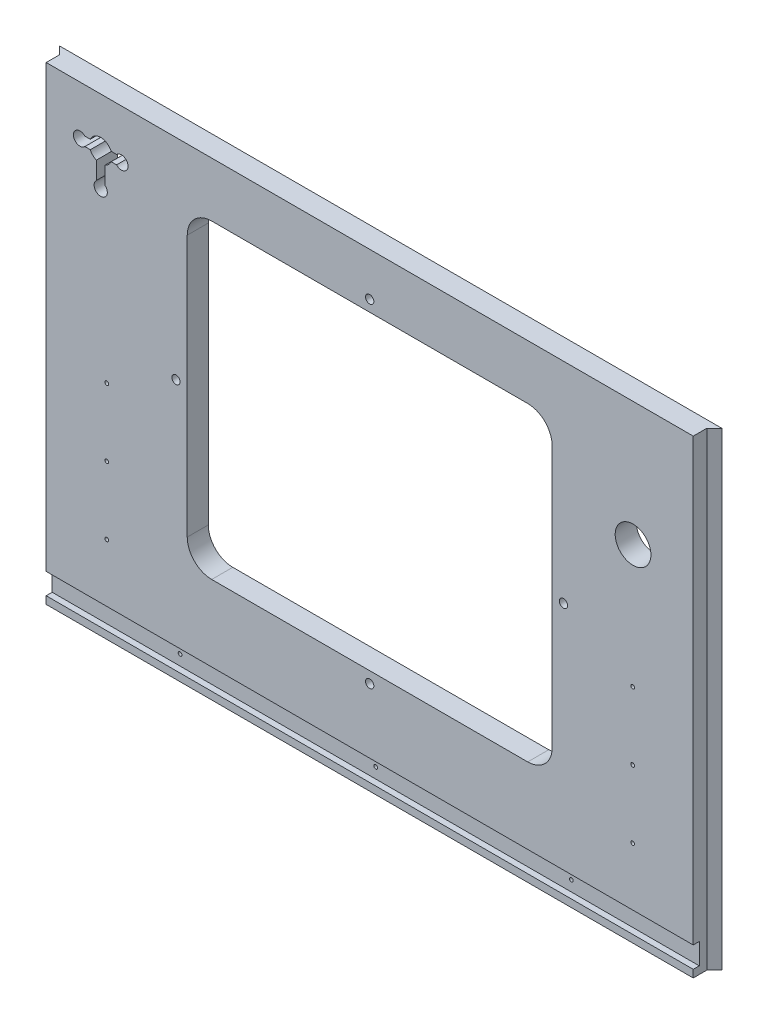
SolidWorks part; units mm, degrees
material "Pine"
ref_plane "Front Plane" through (0, 0, 0) normal (0, 0, 1) x (1, 0, 0)
ref_plane "Top Plane" through (0, 0, 0) normal (0, 1, 0) x (1, 0, 0)
ref_plane "Right Plane" through (0, 0, 0) normal (1, 0, 0) x (0, 0, -1)
sketch "Sketch1" plane through (0, 0, 0) normal (0, 0, 1) x (1, 0, 0)
  line L0 (8932.6508, -5243.5125) -> (10226.1458, -5243.5125)
  line L1 (9086.3208, -4722.0918) -> (10222.9708, -4853.7812)
  line L2 (8914.8708, -6342.0625) -> (10197.5708, -6342.0625)
  line L3 (8914.8708, -5808.6625) -> (10197.5708, -5808.6625)
  line L4 (8919.6333, -5253.0375) -> (10218.2083, -5253.0375)
  line L5 (9134.2633, -4656.1375) -> (9134.2633, -4638.3575)
  line L6 (9091.0833, -4638.3575) -> (9134.2633, -4638.3575)
  line L7 (9091.0833, -4567.2375) -> (9091.0833, -4638.3575)
  line L8 (9134.2633, -4656.1375) -> (9581.3033, -4656.1375)
  line L9 (9091.0833, -4567.2375) -> (9624.4833, -4567.2375)
  line L10 (9581.3033, -4656.1375) -> (9581.3033, -4638.3575)
  line L11 (9581.3033, -4638.3575) -> (9624.4833, -4638.3575)
  line L12 (9624.4833, -4567.2375) -> (9624.4833, -4638.3575)
  line L13 (8932.6508, -5225.7325) -> (9344.9775, -5225.7325)
  line L14 (8932.6508, -5256.2125) -> (8932.6508, -5243.5125)
  line L15 (8911.6958, -5256.2125) -> (8932.6508, -5256.2125)
  line L16 (8914.8708, -4722.0918) -> (9086.3208, -4722.0918)
  line L17 (8911.6958, -4715.5913) -> (8932.6508, -4715.5913)
  line L18 (8914.8708, -6342.0625) -> (8914.8708, -5808.6625)
  line L19 (12082.9917, -4722.0918) -> (10946.3417, -4853.7812)
  line L20 (12236.6617, -5243.5125) -> (10943.1667, -5243.5125)
  line L21 (10951.1042, -5253.0375) -> (12249.6792, -5253.0375)
  line L22 (10838.3917, -5656.2625) -> (11308.2917, -5656.2625)
  line L23 (10838.3917, -5719.7625) -> (11308.2917, -5719.7625)
  line L24 (10838.3917, -5742.5368) -> (11308.2917, -5742.5368)
  line L25 (10806.6417, -6342.0625) -> (11340.0417, -6342.0625)
  line L26 (10803.4667, -6335.7125) -> (11343.2167, -6335.7125)
  line L27 (10803.4667, -6317.9325) -> (11343.2167, -6317.9325)
  line L28 (10943.1667, -5225.7325) -> (11376.4483, -5225.7325)
  line L29 (11506.7292, -4754.5625) -> (10806.6417, -4827.5875)
  line L30 (11506.7292, -4567.2375) -> (11506.7292, -4754.5625)
  line L31 (10806.6417, -4567.2375) -> (10806.6417, -4827.5875)
  line L32 (10806.6417, -4567.2375) -> (11506.7292, -4567.2375)
  line L33 (10235.6708, -6329.3625) -> (10245.1958, -6329.3625)
  line L34 (10245.1958, -6329.3625) -> (10254.7208, -6278.5625)
  line L35 (10302.3458, -6329.3625) -> (10311.8708, -6278.5625)
  line L36 (10302.3458, -6329.3625) -> (10292.8208, -6329.3625)
  line L37 (10245.1958, -5821.3625) -> (10254.7208, -5872.1625)
  line L38 (10235.6708, -5821.3625) -> (10245.1958, -5821.3625)
  line L39 (10292.8208, -5821.3625) -> (10302.3458, -5821.3625)
  line L40 (10302.3458, -5821.3625) -> (10311.8708, -5872.1625)
  line L41 (10235.6708, -5821.3625) -> (10235.6708, -6329.3625)
  line L42 (10254.7208, -5872.1625) -> (10254.7208, -6278.5625)
  line L43 (10311.8708, -5872.1625) -> (10311.8708, -6278.5625)
  line L44 (10292.8208, -5821.3625) -> (10292.8208, -6329.3625)
  line L45 (8932.6508, -5225.7325) -> (8932.6508, -4715.5913)
  line L46 (8911.6958, -4715.5913) -> (8911.6958, -5256.2125)
  line L47 (8914.8708, -5248.275) -> (8914.8708, -4722.0918)
  line L48 (8919.6333, -5253.0375) -> (8914.8708, -5248.275)
  line L49 (8914.8708, -5145.0875) -> (8937.426, -5145.0875)
  line L50 (8914.8708, -5202.2375) -> (8937.426, -5202.2375)
  line L51 (10838.3917, -5656.2625) -> (10838.3917, -5719.7625)
  line L52 (10832.0417, -5736.1868) -> (10856.1717, -5736.1868)
  line L53 (10806.6417, -6342.0625) -> (10806.6417, -5818.7368)
  line L54 (10832.0417, -5649.9125) -> (10856.1717, -5649.9125)
  line L55 (10832.0417, -5726.1125) -> (10856.1717, -5726.1125)
  line L56 (10806.6417, -5818.7368) -> (10833.9015, -5818.7368)
  line L57 (10832.0417, -5806.0442) -> (10851.6815, -5806.0442)
  line L58 (10856.1717, -5801.5541) -> (10856.1717, -5736.1868)
  line L59 (10838.3917, -5814.2467) -> (10838.3917, -5742.5368)
  line L60 (10832.0417, -5806.0442) -> (10832.0417, -5736.1868)
  line L61 (10803.4667, -6317.9325) -> (10803.4667, -6335.7125)
  line L62 (10197.5708, -5808.6625) -> (10197.5708, -6342.0625)
  line L63 (9762.3842, -6348.4125) -> (9762.3842, -5802.3125)
  line L64 (9780.1642, -6348.4125) -> (9762.3842, -6348.4125)
  line L65 (9780.1642, -5802.3125) -> (9780.1642, -6348.4125)
  line L66 (9762.3842, -5802.3125) -> (9780.1642, -5802.3125)
  line L67 (9332.2775, -6348.4125) -> (9332.2775, -5802.3125)
  line L68 (9332.2775, -6348.4125) -> (9350.0575, -6348.4125)
  line L69 (9350.0575, -5802.3125) -> (9350.0575, -6348.4125)
  line L70 (9332.2775, -5802.3125) -> (9350.0575, -5802.3125)
  line L71 (9993.8374, -6061.075) -> (9993.8374, -6045.2418)
  line L72 (9998.5999, -6065.8375) -> (10014.4331, -6065.8375)
  line L73 (9998.5999, -6084.8875) -> (10014.4331, -6084.8875)
  line L74 (9993.8374, -6105.4832) -> (9993.8374, -6089.65)
  line L75 (9974.7874, -6105.4832) -> (9974.7874, -6089.65)
  line L76 (9954.1917, -6084.8875) -> (9970.0249, -6084.8875)
  line L77 (9974.7874, -6061.075) -> (9974.7874, -6045.2418)
  line L78 (9954.1917, -6065.8375) -> (9970.0249, -6065.8375)
  line L79 (10793.9417, -6237.2875) -> (10816.4969, -6237.2875)
  line L80 (10793.9417, -6294.4375) -> (10816.4969, -6294.4375)
  line L81 (10856.1717, -5649.9125) -> (10856.1717, -5726.1125)
  line L82 (10832.0417, -5726.1125) -> (10832.0417, -5649.9125)
  line L83 (10226.1458, -5225.7325) -> (10226.1458, -5243.5125)
  line L84 (10205.1908, -5257.8) -> (10205.1908, -4844.2499)
  line L85 (10230.9083, -4844.2499) -> (10230.9083, -5257.8)
  line L86 (10205.1908, -5257.8) -> (10230.9083, -5257.8)
  line L87 (10205.1908, -4844.2499) -> (10230.9083, -4844.2499)
  line L88 (10946.3417, -5176.8375) -> (10968.8969, -5176.8375)
  line L89 (9349.4676, -5141.9125) -> (9358.2674, -5141.9125)
  line L90 (10946.3417, -5119.6875) -> (10968.8969, -5119.6875)
  line L91 (9929.011, -4660.9635) -> (10066.0807, -4660.9635)
  line L92 (9929.011, -4678.7435) -> (10066.0807, -4678.7435)
  line L93 (10943.1667, -5225.7325) -> (10943.1667, -5243.5125)
  line L94 (10946.3417, -5248.275) -> (10951.1042, -5253.0375)
  line L95 (10946.3417, -5257.8063) -> (10946.3417, -4849.0188)
  line L96 (10964.1217, -5257.8) -> (10964.1217, -4844.2499)
  line L97 (10938.4042, -4844.2499) -> (10938.4042, -5257.8)
  line L98 (10938.4042, -5257.8) -> (10964.1217, -5257.8)
  line L99 (10964.1217, -4844.2499) -> (10938.4042, -4844.2499)
  line L100 (10344.8908, -4560.8875) -> (10369.0208, -4560.8875)
  line L101 (10344.8908, -4560.8875) -> (10369.0208, -4560.8875)
  line L102 (10800.2917, -4560.8875) -> (10824.4217, -4560.8875)
  line L103 (10200.4156, -5119.6875) -> (10222.9708, -5119.6875)
  line L104 (10200.4156, -5176.8375) -> (10222.9708, -5176.8375)
  line L105 (9344.9775, -5146.4026) -> (9344.9775, -5225.7325)
  line L106 (10344.8908, -4560.8875) -> (10344.8908, -4833.9375)
  line L107 (9792.8642, -5225.7325) -> (9792.8642, -5146.4026)
  line L108 (9362.7575, -5225.7325) -> (9775.0842, -5225.7325)
  line L109 (9680.3633, -4761.8396) -> (9680.3633, -4559.9604)
  line L110 (9656.2333, -4559.9604) -> (9680.3633, -4559.9604)
  line L111 (9656.2333, -4761.8396) -> (9680.3633, -4761.8396)
  line L112 (9656.2333, -4761.8396) -> (9656.2333, -4559.9604)
  line L113 (9779.5743, -5141.9125) -> (9788.374, -5141.9125)
  line L114 (10070.5708, -4665.4536) -> (10070.5708, -4674.2534)
  line L115 (9924.5208, -4674.2534) -> (9924.5208, -4665.4536)
  line L116 (12127.4417, -6188.3925) -> (12205.5015, -6188.3925)
  line L117 (12209.9917, -6170.6125) -> (12209.9917, -6183.9024)
  line L118 (9792.8642, -5225.7325) -> (10226.1458, -5225.7325)
  line L119 (9662.5833, -4754.5625) -> (10362.6708, -4827.5875)
  line L120 (9662.5833, -4567.2375) -> (9662.5833, -4754.5625)
  line L121 (10362.6708, -4567.2375) -> (10362.6708, -4827.5875)
  line L122 (9662.5833, -4567.2375) -> (10362.6708, -4567.2375)
  line L123 (10824.4217, -4833.9375) -> (10800.2917, -4833.9375)
  line L124 (10800.2917, -4833.9375) -> (10800.2917, -4560.8875)
  line L125 (10824.4217, -4560.8875) -> (10824.4217, -4833.9375)
  line L126 (10344.8908, -4833.9375) -> (10369.0208, -4833.9375)
  line L127 (10369.0208, -4833.9375) -> (10369.0208, -4560.8875)
  line L128 (10222.9708, -5248.275) -> (10218.2083, -5253.0375)
  line L129 (10222.9708, -5257.8063) -> (10222.9708, -4849.0188)
  line L130 (11734.6544, -5701.375) -> (11739.2301, -5701.375)
  line L131 (9362.7575, -5225.7325) -> (9362.7575, -5146.4026)
  line L132 (9775.0842, -5146.4026) -> (9775.0842, -5225.7325)
  line L133 (11761.3864, -5701.375) -> (11756.8282, -5701.375)
  line L134 (11734.6544, -5693.755) -> (11739.2301, -5693.755)
  line L135 (11761.4039, -5693.755) -> (11756.8282, -5693.755)
  line L136 (11734.6544, -5701.375) -> (11739.2301, -5701.375)
  line L137 (11744.3462, -5721.3024) -> (11744.3462, -5706.4179)
  line L138 (11751.7122, -5721.3024) -> (11751.7122, -5706.4179)
  line L139 (11740.0917, -6170.6125) -> (11740.0917, -6183.9024)
  line L140 (11689.2917, -6188.3925) -> (11822.6417, -6188.3925)
  line L141 (11689.2917, -6348.4093) -> (11689.2917, -6164.2657)
  line L142 (11689.2917, -6164.2657) -> (11746.4417, -6164.2657)
  line L143 (11746.4417, -6164.2657) -> (11746.4417, -6188.3925)
  line L144 (11689.2917, -6164.2657) -> (11746.4417, -6164.2657)
  line L145 (11340.0417, -5818.7368) -> (11340.0417, -6342.0625)
  line L146 (11290.5117, -5726.1125) -> (11314.6417, -5726.1125)
  line L147 (11290.5117, -5649.9125) -> (11290.5117, -5726.1125)
  line L148 (11340.0417, -5818.7368) -> (11312.7818, -5818.7368)
  line L149 (11314.6417, -5806.0442) -> (11295.0018, -5806.0442)
  line L150 (11290.5117, -5801.5541) -> (11290.5117, -5736.1868)
  line L151 (11308.2917, -5814.2467) -> (11308.2917, -5742.5368)
  line L152 (11314.6417, -5806.0442) -> (11314.6417, -5736.1868)
  line L153 (11290.5117, -5736.1868) -> (11314.6417, -5736.1868)
  line L154 (11848.0417, -6267.1325) -> (11962.3417, -6267.1325)
  line L155 (11962.3417, -6267.1325) -> (11962.3417, -6203.6325)
  line L156 (11343.2167, -6317.9325) -> (11343.2167, -6335.7125)
  line L157 (11365.4417, -5656.2625) -> (11365.4417, -5719.7625)
  line L158 (11365.4417, -5656.2625) -> (11479.7417, -5656.2625)
  line L159 (11778.1917, -6071.3937) -> (11802.3217, -6071.3937)
  line L160 (11314.6417, -5726.1125) -> (11314.6417, -5649.9125)
  line L161 (11314.6417, -5649.9125) -> (11290.5117, -5649.9125)
  line L162 (11308.2917, -5719.7625) -> (11308.2917, -5656.2625)
  line L163 (11689.2917, -6348.4093) -> (11713.4217, -6348.4093)
  line L164 (12203.6417, -6164.2657) -> (12260.7917, -6164.2657)
  line L165 (11713.4217, -6348.4093) -> (11713.4217, -6164.2657)
  line L166 (11695.6417, -6342.0625) -> (11695.6417, -6170.6125)
  line L167 (11695.6417, -6048.5337) -> (11699.4517, -6052.3437)
  line L168 (11822.6417, -6292.5325) -> (11822.6417, -6188.3925)
  line L169 (11695.6417, -6342.0625) -> (11695.6417, -6170.6125)
  line L170 (11848.0417, -6203.6325) -> (11962.3417, -6203.6325)
  line L171 (11848.0417, -6203.6325) -> (11848.0417, -6267.1325)
  line L172 (11987.7417, -6267.1325) -> (11987.7417, -6203.6325)
  line L173 (11784.5417, -6077.7437) -> (11784.5417, -6141.2438)
  line L174 (11517.8417, -5656.2625) -> (11632.1417, -5656.2625)
  line L175 (11632.1417, -5656.2625) -> (11632.1417, -5719.7625)
  line L176 (11632.1417, -5719.7625) -> (11517.8417, -5719.7625)
  line L177 (11517.8417, -5719.7625) -> (11517.8417, -5656.2625)
  line L178 (11692.4667, -6028.2137) -> (11692.4667, -6045.9937)
  line L179 (11695.6417, -5979.3188) -> (11718.1969, -5979.3188)
  line L180 (11695.6417, -5922.1687) -> (11718.1969, -5922.1687)
  line L181 (11821.0415, -5722.9375) -> (11821.0415, -5943.6)
  line L182 (11687.7042, -5651.5) -> (11701.9917, -5651.5)
  line L183 (11687.7042, -5651.5) -> (11687.7042, -6055.5251)
  line L184 (11687.7042, -6055.5251) -> (11701.9917, -6055.5251)
  line L185 (11701.9917, -6055.5251) -> (11701.9917, -5651.5)
  line L186 (11695.6417, -6055.2013) -> (11695.6417, -5649.595)
  line L187 (11695.6417, -5656.2625) -> (11695.6417, -6048.5337)
  line L188 (11695.6417, -6170.6125) -> (11740.0917, -6170.6125)
  line L189 (12203.6417, -6164.2657) -> (12203.6417, -6188.3925)
  line L190 (12254.4417, -6342.0625) -> (12254.4417, -6170.6125)
  line L191 (12129.0419, -5943.6) -> (12129.0419, -5722.9375)
  line L192 (12254.4417, -6048.5337) -> (12250.6317, -6052.3437)
  line L193 (12257.6167, -6045.9937) -> (12257.6167, -6028.2137)
  line L194 (12248.0917, -5651.5) -> (12262.3792, -5651.5)
  line L195 (12262.3792, -5651.5) -> (12262.3792, -6055.5251)
  line L196 (12262.3792, -6055.5251) -> (12248.0917, -6055.5251)
  line L197 (12248.0917, -6055.5251) -> (12248.0917, -5651.5)
  line L198 (12254.4417, -6141.2438) -> (12254.4417, -6077.7437)
  line L199 (12236.6617, -6164.2657) -> (12260.7917, -6164.2657)
  line L200 (12102.0417, -6267.1325) -> (11987.7417, -6267.1325)
  line L201 (11330.1865, -6237.2875) -> (11352.7417, -6237.2875)
  line L202 (11330.1865, -6294.4375) -> (11352.7417, -6294.4375)
  line L203 (11474.6617, -5851.8425) -> (11492.4417, -5851.8425)
  line L204 (11474.6617, -5808.6625) -> (11474.6617, -5851.8425)
  line L205 (11403.5417, -5808.6625) -> (11474.6617, -5808.6625)
  line L206 (11492.4417, -5851.8425) -> (11492.4417, -6298.8825)
  line L207 (11403.5417, -6342.0625) -> (11403.5417, -5808.6625)
  line L208 (11474.6617, -6298.8825) -> (11492.4417, -6298.8825)
  line L209 (11474.6617, -6342.0625) -> (11474.6617, -6298.8825)
  line L210 (11403.5417, -6342.0625) -> (11474.6617, -6342.0625)
  line L211 (11619.4417, -5851.8425) -> (11601.6617, -5851.8425)
  line L212 (11601.6617, -5808.6625) -> (11601.6617, -5851.8425)
  line L213 (11530.5417, -5808.6625) -> (11601.6617, -5808.6625)
  line L214 (11619.4417, -5851.8425) -> (11619.4417, -6298.8825)
  line L215 (11530.5417, -6342.0625) -> (11530.5417, -5808.6625)
  line L216 (11619.4417, -6298.8825) -> (11601.6617, -6298.8825)
  line L217 (11601.6617, -6342.0625) -> (11601.6617, -6298.8825)
  line L218 (11530.5417, -6342.0625) -> (11601.6617, -6342.0625)
  line L219 (11479.7417, -5719.7625) -> (11479.7417, -5656.2625)
  line L220 (11365.4417, -5719.7625) -> (11479.7417, -5719.7625)
  line L221 (11778.1917, -6147.5937) -> (11802.3217, -6147.5937)
  line L222 (11802.3217, -6071.3937) -> (11802.3217, -6147.5937)
  line L223 (11778.1917, -6147.5937) -> (11778.1917, -6071.3937)
  line L224 (12254.4417, -5922.1687) -> (12231.8865, -5922.1687)
  line L225 (12254.4417, -5979.3188) -> (12231.8865, -5979.3188)
  line L226 (12254.4417, -6055.2013) -> (12254.4417, -5649.595)
  line L227 (12254.4417, -6048.5337) -> (12254.4417, -5656.2625)
  line L228 (11841.6917, -5702.2873) -> (12108.3917, -5702.2873)
  line L229 (11822.6417, -6292.5325) -> (12127.4417, -6292.5325)
  line L230 (12127.4417, -6292.5325) -> (12127.4417, -6188.3925)
  line L231 (12254.4417, -6170.6125) -> (12209.9917, -6170.6125)
  line L232 (11695.6417, -6342.0625) -> (12254.4417, -6342.0625)
  line L233 (12236.6617, -6348.4093) -> (12260.7917, -6348.4093)
  line L234 (12260.7917, -6348.4093) -> (12260.7917, -6164.2657)
  line L235 (12236.6617, -6348.4093) -> (12236.6617, -6164.2657)
  line L236 (12102.0417, -6203.6325) -> (12102.0417, -6267.1325)
  line L237 (11987.7417, -6203.6325) -> (12102.0417, -6203.6325)
  line L238 (12236.6617, -6147.5937) -> (12236.6617, -6071.3937)
  line L239 (12203.6417, -6188.3925) -> (12260.7917, -6188.3925)
  line L240 (11098.7417, -4665.4536) -> (11098.7417, -4674.2534)
  line L241 (11394.2283, -5146.4026) -> (11394.2283, -5225.7325)
  line L242 (11376.4483, -5225.7325) -> (11376.4483, -5146.4026)
  line L243 (11394.2283, -5225.7325) -> (11806.555, -5225.7325)
  line L244 (11841.6917, -5964.2502) -> (12108.3917, -5964.2502)
  line L245 (12236.6617, -6147.5937) -> (12260.7917, -6147.5937)
  line L246 (12236.6617, -5256.2125) -> (12236.6617, -5243.5125)
  line L247 (12260.7917, -6147.5937) -> (12260.7917, -6071.3937)
  line L248 (12260.7917, -6071.3937) -> (12236.6617, -6071.3937)
  line L249 (12254.4417, -6077.7437) -> (11784.5417, -6077.7437)
  line L250 (11784.5417, -6141.2438) -> (12254.4417, -6141.2438)
  line L252 (12254.4417, -5656.2625) -> (11695.6417, -5656.2625)
  line L253 (11699.4517, -6052.3437) -> (12250.6317, -6052.3437)
  line L254 (11692.4667, -6045.9937) -> (12257.6167, -6045.9937)
  line L255 (11692.4667, -6028.2137) -> (12257.6167, -6028.2137)
  line L256 (11824.335, -5146.4026) -> (11824.335, -5225.7325)
  line L257 (11811.0451, -5141.9125) -> (11819.8449, -5141.9125)
  line L258 (11244.7917, -4674.2534) -> (11244.7917, -4665.4536)
  line L259 (11806.555, -5225.7325) -> (11806.555, -5146.4026)
  line L260 (11488.9492, -4761.8396) -> (11488.9492, -4559.9604)
  line L261 (11488.9492, -4559.9604) -> (11513.0792, -4559.9604)
  line L262 (11488.9492, -4761.8396) -> (11513.0792, -4761.8396)
  line L263 (11513.0792, -4761.8396) -> (11513.0792, -4559.9604)
  line L264 (11240.3015, -4660.9635) -> (11103.2318, -4660.9635)
  line L265 (11103.2318, -4678.7435) -> (11240.3015, -4678.7435)
  line L266 (12236.6617, -5225.7325) -> (12236.6617, -4715.5913)
  line L267 (12257.6167, -4715.5913) -> (12257.6167, -5256.2125)
  line L268 (12254.4417, -5248.275) -> (12254.4417, -4722.0918)
  line L269 (12236.6617, -5225.7325) -> (11824.335, -5225.7325)
  line L270 (12035.0492, -4656.1375) -> (12035.0492, -4638.3575)
  line L271 (12078.2292, -4638.3575) -> (12035.0492, -4638.3575)
  line L272 (12078.2292, -4567.2375) -> (12078.2292, -4638.3575)
  line L273 (12035.0492, -4656.1375) -> (11588.0092, -4656.1375)
  line L274 (11544.8292, -4567.2375) -> (12078.2292, -4567.2375)
  line L275 (11588.0092, -4656.1375) -> (11588.0092, -4638.3575)
  line L276 (11544.8292, -4638.3575) -> (11588.0092, -4638.3575)
  line L277 (11544.8292, -4567.2375) -> (11544.8292, -4638.3575)
  line L278 (12249.6792, -5253.0375) -> (12254.4417, -5248.275)
  line L280 (12257.6167, -5256.2125) -> (12236.6617, -5256.2125)
  line L281 (12231.8865, -5145.0875) -> (12254.4417, -5145.0875)
  line L282 (12231.8865, -5202.2375) -> (12254.4417, -5202.2375)
  line L283 (12236.6617, -4715.5913) -> (12257.6167, -4715.5913)
  line L284 (12082.9917, -4722.0918) -> (12254.4417, -4722.0918)
  line L285 (11380.9385, -5141.9125) -> (11389.7382, -5141.9125)
  circle A0 centre (8923.7608, -4778.9042) radius 1.5875
  circle A1 centre (9062.6598, -4736.3765) radius 2.3685
  circle A2 centre (9051.3958, -6281.7375) radius 22.225
  circle A3 centre (9083.1458, -6249.9875) radius 1.5875
  circle A4 centre (9083.1458, -6313.4875) radius 1.5875
  circle A5 centre (9019.6458, -6249.9875) radius 1.5875
  circle A6 centre (9019.6458, -6313.4875) radius 1.5875
  circle A7 centre (8972.3383, -5202.2375) radius 1.5875
  circle A8 centre (8923.7608, -5015.9708) radius 1.5875
  circle A9 centre (8923.7608, -5134.5042) radius 1.5875
  circle A10 centre (9054.5708, -5234.6225) radius 1.5875
  circle A11 centre (8923.7608, -4897.4375) radius 1.5875
  circle A12 centre (8972.3383, -5087.9375) radius 1.5875
  circle A13 centre (8972.3383, -5145.0875) radius 1.5875
  circle A14 centre (10847.2817, -5668.9625) radius 1.5875
  circle A15 centre (10847.2817, -5707.0625) radius 1.5875
  circle A16 centre (10847.2817, -5755.2368) radius 1.5875
  circle A17 centre (10851.4092, -6237.2875) radius 1.5875
  circle A18 centre (10851.4092, -6294.4375) radius 1.5875
  circle A19 centre (10847.2817, -5793.3442) radius 1.5875
  arc A20 (10833.9015, -5818.7368) -> (10838.3917, -5814.2467) centre (10836.1466, -5816.4918) ccw
  arc A21 (10851.6815, -5806.0442) -> (10856.1717, -5801.5541) centre (10853.9266, -5803.7992) ccw
  circle A22 centre (10882.8417, -6040.4375) radius 1.5875
  circle A23 centre (10882.8417, -6218.2375) radius 1.5875
  circle A24 centre (10882.8417, -5862.6375) radius 1.5875
  circle A25 centre (10908.2417, -6326.8225) radius 1.5875
  circle A26 centre (10908.2417, -6326.8225) radius 1.5875
  circle A27 centre (10851.4092, -6180.1375) radius 1.5875
  circle A28 centre (10815.5317, -4783.4231) radius 1.5875
  circle A29 centre (10815.5317, -4696.9488) radius 1.5875
  circle A30 centre (10815.5317, -4610.4746) radius 1.5875
  circle A31 centre (10979.1323, -4867.0082) radius 2.3685
  circle A32 centre (10190.1802, -4867.0082) radius 2.3685
  circle A33 centre (10955.2317, -4929.9812) radius 1.5875
  circle A34 centre (10955.2317, -5031.5812) radius 1.5875
  circle A35 centre (10214.0808, -4929.9812) radius 1.5875
  circle A36 centre (10214.0808, -5031.5812) radius 1.5875
  circle A37 centre (9341.1675, -6265.8625) radius 1.5875
  circle A38 centre (9771.2742, -5884.8625) radius 1.5875
  circle A39 centre (9771.2742, -6138.8625) radius 1.5875
  circle A40 centre (9771.2742, -6011.8625) radius 1.5875
  arc A41 (10036.2287, -6113.8083) -> (10051.3426, -6111.6033) centre (10042.9639, -6107.0732) ccw
  arc A42 (10051.3426, -6111.6033) -> (10051.3426, -6039.1217) centre (9984.3124, -6075.3625) ccw
  arc A43 (10051.3426, -6039.1217) -> (10036.2287, -6036.9167) centre (10042.9639, -6043.6518) ccw
  arc A44 (10034.5851, -6102.5431) -> (10034.5851, -6048.1819) centre (9984.3124, -6075.3625) ccw
  arc A45 (10034.5851, -6102.5431) -> (10036.2287, -6113.8083) centre (10042.9639, -6107.0732) ccw
  arc A46 (10036.2287, -6036.9167) -> (10034.5851, -6048.1819) centre (10042.9639, -6043.6518) ccw
  arc A47 (9945.8666, -6127.2787) -> (9948.0717, -6142.3927) centre (9952.6018, -6134.0139) ccw
  arc A48 (9948.0717, -6142.3927) -> (10020.5532, -6142.3927) centre (9984.3124, -6075.3625) ccw
  arc A49 (10020.5532, -6142.3927) -> (10022.7583, -6127.2787) centre (10016.0231, -6134.0139) ccw
  arc A50 (9957.1319, -6125.6352) -> (10011.493, -6125.6352) centre (9984.3124, -6075.3625) ccw
  arc A51 (9957.1319, -6125.6352) -> (9945.8666, -6127.2787) centre (9952.6018, -6134.0139) ccw
  arc A52 (10022.7583, -6127.2787) -> (10011.493, -6125.6352) centre (10016.0231, -6134.0139) ccw
  arc A53 (9932.3962, -6036.9167) -> (9917.2822, -6039.1217) centre (9925.661, -6043.6518) ccw
  arc A54 (9917.2822, -6039.1217) -> (9917.2822, -6111.6033) centre (9984.3124, -6075.3625) ccw
  arc A55 (9917.2822, -6111.6033) -> (9932.3962, -6113.8083) centre (9925.661, -6107.0732) ccw
  arc A56 (9934.0398, -6048.1819) -> (9934.0398, -6102.5431) centre (9984.3124, -6075.3625) ccw
  arc A57 (9934.0398, -6048.1819) -> (9932.3962, -6036.9167) centre (9925.661, -6043.6518) ccw
  arc A58 (9932.3962, -6113.8083) -> (9934.0398, -6102.5431) centre (9925.661, -6107.0732) ccw
  arc A59 (9945.8666, -6023.4463) -> (9957.1319, -6025.0898) centre (9952.6018, -6016.7111) ccw
  arc A60 (10011.493, -6025.0898) -> (10022.7583, -6023.4463) centre (10016.0231, -6016.7111) ccw
  arc A61 (10011.493, -6025.0898) -> (9957.1319, -6025.0898) centre (9984.3124, -6075.3625) ccw
  arc A62 (9948.0717, -6008.3323) -> (9945.8666, -6023.4463) centre (9952.6018, -6016.7111) ccw
  arc A63 (10020.5532, -6008.3323) -> (9948.0717, -6008.3323) centre (9984.3124, -6075.3625) ccw
  arc A64 (10022.7583, -6023.4463) -> (10020.5532, -6008.3323) centre (10016.0231, -6016.7111) ccw
  arc A65 (10005.0943, -6187.7574) -> (10096.7073, -6096.1443) centre (9984.3124, -6075.3625) ccw
  arc A66 (9993.8374, -6178.3911) -> (10005.0943, -6187.7574) centre (10003.3624, -6178.3911) ccw
  arc A67 (10001.6306, -6169.0249) -> (10077.9748, -6092.6807) centre (9984.3124, -6075.3625) ccw
  arc A68 (10087.3411, -6084.8875) -> (10077.9748, -6092.6807) centre (10087.3411, -6094.4125) ccw
  arc A69 (10001.6306, -6169.0249) -> (9993.8374, -6178.3911) centre (10003.3624, -6178.3911) ccw
  arc A70 (9963.5306, -6187.7574) -> (9974.7874, -6178.3911) centre (9965.2624, -6178.3911) ccw
  arc A71 (9871.9176, -6096.1443) -> (9963.5306, -6187.7574) centre (9984.3124, -6075.3625) ccw
  arc A72 (9881.2838, -6084.8875) -> (9871.9176, -6096.1443) centre (9881.2838, -6094.4125) ccw
  arc A73 (9890.65, -6092.6807) -> (9966.9943, -6169.0249) centre (9984.3124, -6075.3625) ccw
  arc A74 (9974.7874, -6178.3911) -> (9966.9943, -6169.0249) centre (9965.2624, -6178.3911) ccw
  arc A75 (9890.65, -6092.6807) -> (9881.2838, -6084.8875) centre (9881.2838, -6094.4125) ccw
  arc A76 (9871.9176, -6054.5807) -> (9881.2838, -6065.8375) centre (9881.2838, -6056.3125) ccw
  arc A77 (9963.5306, -5962.9676) -> (9871.9176, -6054.5807) centre (9984.3124, -6075.3625) ccw
  arc A78 (9974.7874, -5972.3339) -> (9963.5306, -5962.9676) centre (9965.2624, -5972.3339) ccw
  arc A79 (9966.9943, -5981.7001) -> (9890.65, -6058.0443) centre (9984.3124, -6075.3625) ccw
  arc A80 (9881.2838, -6065.8375) -> (9890.65, -6058.0443) centre (9881.2838, -6056.3125) ccw
  arc A81 (9966.9943, -5981.7001) -> (9974.7874, -5972.3339) centre (9965.2624, -5972.3339) ccw
  arc A82 (10077.9748, -6058.0443) -> (10087.3411, -6065.8375) centre (10087.3411, -6056.3125) ccw
  arc A83 (9993.8374, -5972.3339) -> (10001.6306, -5981.7001) centre (10003.3624, -5972.3339) ccw
  arc A84 (10077.9748, -6058.0443) -> (10001.6306, -5981.7001) centre (9984.3124, -6075.3625) ccw
  arc A85 (10087.3411, -6065.8375) -> (10096.7073, -6054.5807) centre (10087.3411, -6056.3125) ccw
  arc A86 (10096.7073, -6054.5807) -> (10005.0943, -5962.9676) centre (9984.3124, -6075.3625) ccw
  arc A87 (10005.0943, -5962.9676) -> (9993.8374, -5972.3339) centre (10003.3624, -5972.3339) ccw
  arc A88 (10014.4331, -6065.8375) -> (10018.7361, -6059.0339) centre (10014.4331, -6061.075) ccw
  arc A89 (10018.7361, -6059.0339) -> (10000.641, -6040.9388) centre (9984.3124, -6075.3625) ccw
  arc A90 (10000.641, -6040.9388) -> (9993.8374, -6045.2418) centre (9998.5999, -6045.2418) ccw
  arc A91 (9993.8374, -6061.075) -> (9998.5999, -6065.8375) centre (9998.5999, -6061.075) ccw
  arc A92 (9993.8374, -6105.4832) -> (10000.641, -6109.7862) centre (9998.5999, -6105.4832) ccw
  arc A93 (10000.641, -6109.7862) -> (10018.7361, -6091.6911) centre (9984.3124, -6075.3625) ccw
  arc A94 (10018.7361, -6091.6911) -> (10014.4331, -6084.8875) centre (10014.4331, -6089.65) ccw
  arc A95 (9998.5999, -6084.8875) -> (9993.8374, -6089.65) centre (9998.5999, -6089.65) ccw
  arc A96 (9954.1917, -6084.8875) -> (9949.8888, -6091.6911) centre (9954.1917, -6089.65) ccw
  arc A97 (9949.8888, -6091.6911) -> (9967.9839, -6109.7862) centre (9984.3124, -6075.3625) ccw
  arc A98 (9967.9839, -6109.7862) -> (9974.7874, -6105.4832) centre (9970.0249, -6105.4832) ccw
  arc A99 (9974.7874, -6089.65) -> (9970.0249, -6084.8875) centre (9970.0249, -6089.65) ccw
  arc A100 (9970.0249, -6065.8375) -> (9974.7874, -6061.075) centre (9970.0249, -6061.075) ccw
  arc A101 (9949.8888, -6059.0339) -> (9954.1917, -6065.8375) centre (9954.1917, -6061.075) ccw
  arc A102 (9967.9839, -6040.9388) -> (9949.8888, -6059.0339) centre (9984.3124, -6075.3625) ccw
  arc A103 (9974.7874, -6045.2418) -> (9967.9839, -6040.9388) centre (9970.0249, -6045.2418) ccw
  arc A104 (10096.7073, -6096.1443) -> (10087.3411, -6084.8875) centre (10087.3411, -6094.4125) ccw
  circle A105 centre (9771.2742, -6265.8625) radius 1.5875
  circle A106 centre (9341.1675, -5884.8625) radius 1.5875
  circle A107 centre (9341.1675, -6138.8625) radius 1.5875
  circle A108 centre (9341.1675, -6011.8625) radius 1.5875
  circle A109 centre (11037.2315, -4887.5494) radius 15.0812
  arc A110 (9349.4676, -5141.9125) -> (9344.9775, -5146.4026) centre (9347.2226, -5144.1576) ccw
  arc A111 (9362.7575, -5146.4026) -> (9358.2674, -5141.9125) centre (9360.5124, -5144.1576) ccw
  circle A112 centre (9946.7458, -4669.8535) radius 1.5875
  arc A113 (9924.5208, -4674.2534) -> (9929.011, -4678.7435) centre (9926.7659, -4676.4984) ccw
  circle A114 centre (11003.8092, -5176.8375) radius 1.5875
  circle A115 centre (11003.8092, -5119.6875) radius 1.5875
  circle A116 centre (10353.7808, -4696.9488) radius 1.5875
  circle A117 centre (10353.7808, -4610.4746) radius 1.5875
  circle A118 centre (10353.7808, -4783.4231) radius 1.5875
  circle A119 centre (11003.8092, -5062.5375) radius 1.5875
  circle A120 centre (9353.8675, -5160.9625) radius 1.5875
  circle A121 centre (9638.7708, -5234.6225) radius 1.5875
  circle A122 centre (9671.4733, -4724.1144) radius 1.5875
  circle A123 centre (9671.4733, -4661.3637) radius 1.5875
  circle A124 centre (9671.4733, -4598.6129) radius 1.5875
  arc A125 (9792.8642, -5146.4026) -> (9788.374, -5141.9125) centre (9790.6191, -5144.1576) ccw
  arc A126 (9779.5743, -5141.9125) -> (9775.0842, -5146.4026) centre (9777.3292, -5144.1576) ccw
  circle A127 centre (10048.3458, -4669.8535) radius 1.5875
  arc A128 (10070.5708, -4665.4536) -> (10066.0807, -4660.9635) centre (10068.3258, -4663.2086) ccw
  arc A129 (10066.0807, -4678.7435) -> (10070.5708, -4674.2534) centre (10068.3258, -4676.4984) ccw
  circle A130 centre (9997.5458, -4669.8535) radius 1.5875
  arc A131 (9929.011, -4660.9635) -> (9924.5208, -4665.4536) centre (9926.7659, -4663.2086) ccw
  circle A132 centre (10132.081, -4887.5494) radius 15.0812
  circle A133 centre (10165.5033, -5176.8375) radius 1.5875
  circle A134 centre (10165.5033, -5119.6875) radius 1.5875
  circle A135 centre (9486.3708, -5234.6225) radius 1.5875
  circle A136 centre (10165.5033, -5062.5375) radius 1.5875
  circle A137 centre (9206.9708, -5234.6225) radius 1.5875
  circle A138 centre (10070.5708, -5234.6225) radius 1.5875
  circle A139 centre (9918.1708, -5234.6225) radius 1.5875
  circle A140 centre (9783.9742, -5160.9625) radius 1.5875
  circle A141 centre (9783.9742, -5193.9825) radius 1.5875
  circle A142 centre (9353.8675, -5193.9825) radius 1.5875
  circle A143 centre (11073.3417, -6326.8225) radius 1.5875
  circle A144 centre (11073.3417, -6326.8225) radius 1.5875
  circle A145 centre (11295.2742, -6180.1375) radius 1.5875
  circle A146 centre (11295.2742, -6294.4375) radius 1.5875
  circle A147 centre (11295.2742, -6237.2875) radius 1.5875
  circle A148 centre (11975.0417, -5692.775) radius 3.4925
  circle A149 centre (11263.8417, -5862.6375) radius 1.5875
  arc A150 (11739.2301, -5701.375) -> (11744.3462, -5706.4179) centre (11748.0292, -5697.565) ccw
  arc A151 (11751.7122, -5706.4179) -> (11756.8282, -5701.375) centre (11748.0292, -5697.565) ccw
  arc A152 (11744.3462, -5721.3024) -> (11751.7122, -5721.3024) centre (11748.0292, -5725.505) ccw
  arc A153 (11734.6544, -5693.755) -> (11724.9787, -5697.565) centre (11730.5667, -5697.565) ccw
  arc A154 (11756.8282, -5693.755) -> (11739.2301, -5693.755) centre (11748.0292, -5697.565) ccw
  arc A155 (11724.9787, -5697.565) -> (11734.6544, -5701.375) centre (11730.5667, -5697.565) ccw
  arc A156 (11761.3864, -5701.375) -> (11771.0797, -5697.565) centre (11765.4842, -5697.565) ccw
  arc A157 (11771.0797, -5697.565) -> (11761.4039, -5693.755) centre (11765.4917, -5697.565) ccw
  arc A158 (11740.0917, -6183.9024) -> (11744.5818, -6188.3925) centre (11742.3367, -6186.1474) ccw
  arc A159 (12205.5015, -6188.3925) -> (12209.9917, -6183.9024) centre (12207.7466, -6186.1474) ccw
  circle A160 centre (11299.4017, -5793.3442) radius 1.5875
  arc A161 (11308.2917, -5814.2467) -> (11312.7818, -5818.7368) centre (11310.5367, -5816.4918) ccw
  arc A162 (11290.5117, -5801.5541) -> (11295.0018, -5806.0442) centre (11292.7567, -5803.7992) ccw
  circle A163 centre (11704.5317, -6314.149) radius 1.5875
  circle A164 centre (11748.9817, -6208.7125) radius 1.5875
  circle A165 centre (11263.8417, -6218.2375) radius 1.5875
  circle A166 centre (11263.8417, -6040.4375) radius 1.5875
  circle A167 centre (11238.4417, -6326.8225) radius 1.5875
  circle A168 centre (11238.4417, -6326.8225) radius 1.5875
  circle A169 centre (11299.4017, -5668.9625) radius 1.5875
  circle A170 centre (11299.4017, -5707.0625) radius 1.5875
  circle A171 centre (11726.7567, -6179.5025) radius 1.5875
  circle A172 centre (11704.5317, -6199.3198) radius 1.5875
  circle A173 centre (11748.9817, -6272.2125) radius 1.5875
  circle A174 centre (11704.5317, -6256.7344) radius 1.5875
  circle A175 centre (11299.4017, -5755.2368) radius 1.5875
  circle A176 centre (11913.4467, -6301.4225) radius 1.5875
  circle A177 centre (11790.2567, -6301.4225) radius 1.5875
  circle A178 centre (11793.4317, -6128.5437) radius 1.5875
  circle A179 centre (11753.1092, -5865.0188) radius 1.5875
  circle A180 centre (11809.9417, -6037.1038) radius 1.5875
  circle A181 centre (11809.9417, -6037.1038) radius 1.5875
  circle A182 centre (11753.1092, -5922.1687) radius 1.5875
  circle A183 centre (11975.0417, -5973.7625) radius 3.4925
  circle A184 centre (11975.0417, -6037.1038) radius 1.5875
  circle A185 centre (11753.1092, -5979.3188) radius 1.5875
  circle A186 centre (11975.0417, -6037.1038) radius 1.5875
  arc A187 (11841.6917, -5702.2873) -> (11821.0415, -5722.9375) centre (11841.6917, -5722.9375) ccw
  circle A188 centre (11811.5292, -5833.2687) radius 3.4925
  arc A189 (11821.0415, -5943.6) -> (11841.6917, -5964.2502) centre (11841.6917, -5943.6) ccw
  circle A190 centre (12196.9742, -5865.0188) radius 1.5875
  arc A191 (12129.0419, -5722.9375) -> (12108.3917, -5702.2873) centre (12108.3917, -5722.9375) ccw
  circle A192 centre (12036.6367, -6301.4225) radius 1.5875
  circle A193 centre (12159.8267, -6301.4225) radius 1.5875
  circle A194 centre (12138.5542, -5833.2687) radius 3.4925
  circle A195 centre (12197.2917, -5761.0375) radius 15.0812
  circle A196 centre (11793.4317, -6090.4437) radius 1.5875
  circle A197 centre (12196.9742, -5922.1687) radius 1.5875
  arc A198 (12108.3917, -5964.2502) -> (12129.0419, -5943.6) centre (12108.3917, -5943.6) ccw
  circle A199 centre (12196.9742, -5979.3188) radius 1.5875
  circle A200 centre (12201.1017, -6272.2125) radius 1.5875
  circle A201 centre (12245.5517, -6314.149) radius 1.5875
  circle A202 centre (12245.5517, -6256.7344) radius 1.5875
  circle A203 centre (12201.1017, -6208.7125) radius 1.5875
  circle A204 centre (12223.3267, -6179.5025) radius 1.5875
  circle A205 centre (12245.5517, -6199.3198) radius 1.5875
  circle A206 centre (11171.7667, -4669.8535) radius 1.5875
  circle A207 centre (11222.5667, -4669.8535) radius 1.5875
  arc A208 (11240.3015, -4678.7435) -> (11244.7917, -4674.2534) centre (11242.5466, -4676.4984) ccw
  circle A209 centre (11385.3383, -5193.9825) radius 1.5875
  circle A210 centre (12106.6527, -4736.3765) radius 2.3685
  circle A211 centre (12140.1417, -6037.1038) radius 1.5875
  circle A212 centre (12140.1417, -6037.1038) radius 1.5875
  circle A213 centre (12245.5517, -6090.4437) radius 1.5875
  circle A214 centre (12245.5517, -6128.5437) radius 1.5875
  circle A215 centre (11385.3383, -5160.9625) radius 1.5875
  arc A216 (11824.335, -5146.4026) -> (11819.8449, -5141.9125) centre (11822.0899, -5144.1576) ccw
  arc A217 (11811.0451, -5141.9125) -> (11806.555, -5146.4026) centre (11808.8001, -5144.1576) ccw
  circle A218 centre (11815.445, -5193.9825) radius 1.5875
  circle A219 centre (11815.445, -5160.9625) radius 1.5875
  circle A220 centre (11530.5417, -5234.6225) radius 1.5875
  circle A221 centre (11962.3417, -5234.6225) radius 1.5875
  arc A222 (11244.7917, -4665.4536) -> (11240.3015, -4660.9635) centre (11242.5466, -4663.2086) ccw
  circle A223 centre (11682.9417, -5234.6225) radius 1.5875
  circle A224 centre (11497.8392, -4724.1144) radius 1.5875
  circle A225 centre (11497.8392, -4661.3637) radius 1.5875
  circle A226 centre (11497.8392, -4598.6129) radius 1.5875
  circle A227 centre (11120.9667, -4669.8535) radius 1.5875
  arc A228 (11103.2318, -4660.9635) -> (11098.7417, -4665.4536) centre (11100.9867, -4663.2086) ccw
  arc A229 (11098.7417, -4674.2534) -> (11103.2318, -4678.7435) centre (11100.9867, -4676.4984) ccw
  circle A230 centre (12196.9742, -5202.2375) radius 1.5875
  circle A231 centre (12245.5517, -5015.9708) radius 1.5875
  circle A232 centre (12245.5517, -5134.5042) radius 1.5875
  circle A233 centre (12114.7417, -5234.6225) radius 1.5875
  circle A234 centre (12245.5517, -4897.4375) radius 1.5875
  circle A235 centre (12245.5517, -4778.9042) radius 1.5875
  circle A236 centre (12196.9742, -5087.9375) radius 1.5875
  circle A237 centre (12196.9742, -5145.0875) radius 1.5875
  circle A238 centre (11098.7417, -5234.6225) radius 1.5875
  circle A239 centre (11251.1417, -5234.6225) radius 1.5875
  arc A240 (11380.9385, -5141.9125) -> (11376.4483, -5146.4026) centre (11378.6934, -5144.1576) ccw
  arc A241 (11394.2283, -5146.4026) -> (11389.7382, -5141.9125) centre (11391.9833, -5144.1576) ccw
sketch "Sketch2" plane through (0, 0, 0) normal (0, 0, 1) x (1, 0, 0)
  line L0 (11695.6417, -6055.2013) -> (11695.6417, -5649.595) construction
  line L1 (11695.6417, -6052.3437) -> (12254.4417, -6052.3437)
  line L3 (12254.4417, -6052.3437) -> (12254.4417, -5656.2625)
  line L4 (12254.4417, -5656.2625) -> (11695.6417, -5656.2625)
  line L5 (11695.6417, -5656.2625) -> (11695.6417, -6052.3437)
  point P1 (0, 0)
  point P2 (0, 0)
  dimension "D1" = 558.8
extrude "Extrude1" add sketch "Sketch2" against normal blind 17.78
sketch "Sketch3" plane through (0, 0, 0) normal (0, 0, 1) x (1, 0, 0)
  line L0 (11821.0415, -5702.2873) -> (12129.0419, -5702.2873)
  line L1 (12129.0419, -5702.2873) -> (12129.0419, -5964.2502)
  line L2 (12129.0419, -5964.2502) -> (11821.0415, -5964.2502)
  line L3 (11821.0415, -5964.2502) -> (11821.0415, -5702.2873)
  line L4 (11734.6544, -5693.755) -> (11739.2301, -5693.755)
  line L5 (11734.6544, -5701.375) -> (11739.2301, -5701.375)
  line L6 (11744.3462, -5706.4179) -> (11744.3462, -5721.3024)
  line L7 (11751.7122, -5706.4179) -> (11751.7122, -5721.3024)
  line L8 (11756.8282, -5701.375) -> (11761.3864, -5701.375)
  line L9 (11761.3864, -5693.755) -> (11756.8282, -5693.755)
  line L10 (11753.1092, -5865.0188) -> (11753.1092, -5922.1687) construction
  line L11 (11753.1092, -5922.1687) -> (11753.1092, -5979.3188) construction
  line L12 (11695.6417, -5656.2625) -> (11695.6417, -6052.3437) construction
  line L13 (12196.9742, -5865.0188) -> (12196.9742, -5922.1687) construction
  line L14 (12196.9742, -5922.1687) -> (12196.9742, -5979.3188) construction
  line L15 (12254.4417, -6052.3437) -> (12254.4417, -5656.2625) construction
  line L16 (11809.9417, -6037.1038) -> (11975.0417, -6037.1038) construction
  line L17 (11975.0417, -6037.1038) -> (12140.1417, -6037.1038) construction
  line L18 (11975.0417, -6037.1038) -> (11975.0417, -6052.3437) construction
  line L19 (11695.6417, -6052.3437) -> (12254.4417, -6052.3437) construction
  line L20 (11975.0417, -5692.775) -> (11975.0417, -5702.2873) construction
  line L21 (11811.5292, -5833.2688) -> (11821.0415, -5833.2688) construction
  line L22 (11975.0417, -5973.7625) -> (11975.0417, -5964.2502) construction
  line L23 (12138.5542, -5833.2688) -> (12129.0419, -5833.2688) construction
  line L24 (11975.0417, -5692.775) -> (11975.0417, -5656.2625) construction
  line L25 (12254.4417, -5656.2625) -> (11695.6417, -5656.2625) construction
  arc A4 (11734.6544, -5693.755) -> (11734.6544, -5701.375) centre (11730.5667, -5697.565) ccw
  arc A5 (11724.9787, -5697.565) -> (11734.6544, -5701.375) centre (11730.5667, -5697.565) ccw construction
  arc A6 (11739.2301, -5693.755) -> (11756.8282, -5693.755) centre (11748.0292, -5697.565) cw
  arc A7 (11756.8282, -5693.755) -> (11739.2301, -5693.755) centre (11748.0292, -5697.565) ccw construction
  arc A8 (11744.3462, -5721.3024) -> (11751.7122, -5721.3024) centre (11748.0292, -5725.505) ccw
  arc A9 (11744.3462, -5721.3024) -> (11751.7122, -5721.3024) centre (11748.0292, -5725.505) ccw construction
  arc A10 (11739.2301, -5701.375) -> (11744.3462, -5706.4179) centre (11748.0292, -5697.565) ccw
  arc A11 (11739.2301, -5701.375) -> (11744.3462, -5706.4179) centre (11748.0292, -5697.565) ccw construction
  arc A12 (11751.7122, -5706.4179) -> (11756.8282, -5701.375) centre (11748.0292, -5697.565) ccw
  arc A13 (11751.7122, -5706.4179) -> (11756.8282, -5701.375) centre (11748.0292, -5697.565) ccw construction
  arc A14 (11761.3864, -5701.375) -> (11771.0797, -5697.565) centre (11765.4842, -5697.565) ccw
  arc A16 (11761.3864, -5701.375) -> (11771.0797, -5697.565) centre (11765.4842, -5697.565) ccw construction
  arc A17 (11771.0797, -5697.565) -> (11761.3864, -5693.755) centre (11765.4842, -5697.565) ccw
  circle A18 centre (12197.2917, -5761.0375) radius 15.0812
  circle A19 centre (12138.5542, -5833.2688) radius 3.4925
  circle A20 centre (12196.9742, -5865.0188) radius 1.5875
  circle A21 centre (12196.9742, -5922.1687) radius 1.5875
  circle A22 centre (12196.9742, -5979.3188) radius 1.5875
  circle A23 centre (12140.1417, -6037.1038) radius 1.5875
  circle A24 centre (11975.0417, -6037.1038) radius 1.5875
  circle A25 centre (11809.9417, -6037.1038) radius 1.5875
  circle A26 centre (11753.1092, -5979.3188) radius 1.5875
  circle A27 centre (11753.1092, -5922.1687) radius 1.5875
  circle A28 centre (11753.1092, -5865.0188) radius 1.5875
  circle A29 centre (11811.5292, -5833.2688) radius 3.4925
  circle A30 centre (11975.0417, -5973.7625) radius 3.4925
  circle A31 centre (11975.0417, -5692.775) radius 3.4925
  dimension "D1" = 57.4675
  dimension "D2" = 57.4675
  dimension "D3" = 57.15
  dimension "D4" = 36.5125
  dimension "D5" = 308.0004
  dimension "D6" = 9.5123
  dimension "D7" = 261.9629
extrude "Cut-Extrude1" cut sketch "Sketch3" against normal up to surface (17.78 mm away) up to face at (11975.0417, -5854.3031, -17.78)
sketch "Sketch4" plane through (0, 0, 0) normal (0, 0, 1) x (1, 0, 0)
  line L0 (11975.0417, -6028.2137) -> (11695.6417, -6028.2137)
  line L1 (11975.0417, -6028.2137) -> (11975.0417, -6052.3437) construction
  line L2 (11695.6417, -6055.2013) -> (11695.6417, -5649.595) construction
  line L3 (11692.4667, -6028.2137) -> (12257.6167, -6028.2137) construction
  line L4 (11699.4517, -6052.3437) -> (12250.6317, -6052.3437) construction
  line L5 (11695.6417, -6028.2137) -> (11695.6417, -6045.9937)
  line L6 (11695.6417, -6045.9937) -> (12254.4417, -6045.9937)
  line L7 (12254.4417, -6052.3437) -> (12254.4417, -5656.2625) construction
  line L9 (12254.4417, -6045.9937) -> (12254.4417, -6028.2137)
  line L10 (12254.4417, -6028.2137) -> (11975.0417, -6028.2137)
  dimension "D1" = 17.78
extrude "Cut-Extrude2" cut sketch "Sketch4" against normal blind 5.08
sketch "Sketch7" plane through (0, -6052.3437, 0) normal (0, -1, 0) x (1, 0, 0)
  line L0 (11701.9917, -11.43) -> (11701.9917, 0)
  line L1 (11701.9917, 0) -> (11695.6417, 0)
  line L2 (11695.6417, 0) -> (11695.6417, -17.78)
  line L5 (12248.0917, -11.43) -> (12254.4417, -17.78)
  line L10 (11695.6417, -17.78) -> (11701.9917, -11.43)
  line L11 (12248.0917, -11.43) -> (12248.0917, 0)
  line L12 (11695.6417, 0) -> (12254.4417, 0) construction
  line L13 (12248.0917, 0) -> (12254.4417, 0)
  line L14 (12254.4417, 0) -> (12254.4417, -17.78)
  dimension "D1" = 6.35
  dimension "D2" = 6.35
  dimension "D3" = 6.35
  dimension "D4" = 6.35
extrude "Cut-Extrude4" cut sketch "Sketch7" against normal up to surface (396.0813 mm away) up to face at (11975.0417, -5656.2625, -8.89)
fillet "Fillet1" radius 20.6502 4 edges at (11821.0415, -5702.2873, -8.89) (11821.0415, -5964.2502, -8.89) (12129.0419, -5964.2502, -8.89) (12129.0419, -5702.2873, -8.89)
